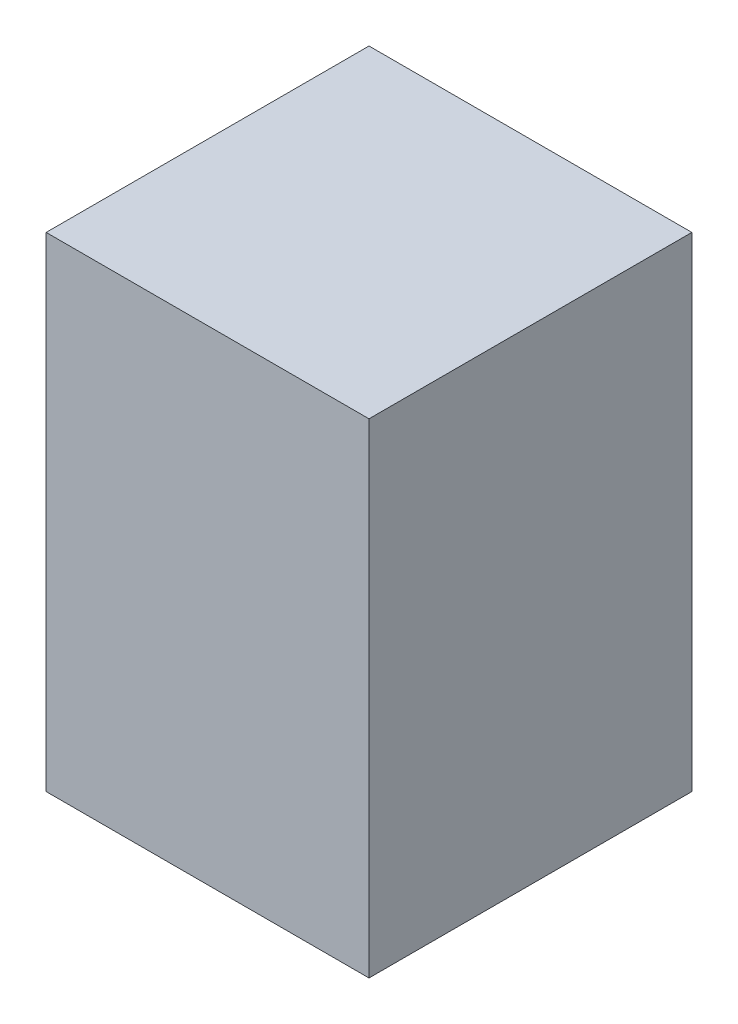
SolidWorks part; units mm, degrees
ref_plane "Front Plane" through (0, 0, 0) normal (0, 0, 1) x (1, 0, 0)
ref_plane "Top Plane" through (0, 0, 0) normal (0, 1, 0) x (1, 0, 0)
ref_plane "Right Plane" through (0, 0, 0) normal (1, 0, 0) x (0, 0, -1)
other "Configuration Table"
sketch "Sketch1" plane through (0, 0, 0) normal (0, 0, 1) x (1, 0, 0)
  line L1 (560, 0) -> (640, 0)
  line L2 (560, 0) -> (560, 120)
  line L3 (560, 120) -> (640, 120)
  line L4 (640, 0) -> (640, 120)
extrude "PRESS_ayak_4_1" add sketch "Sketch1" against normal blind 80 from offset 680 separate body
